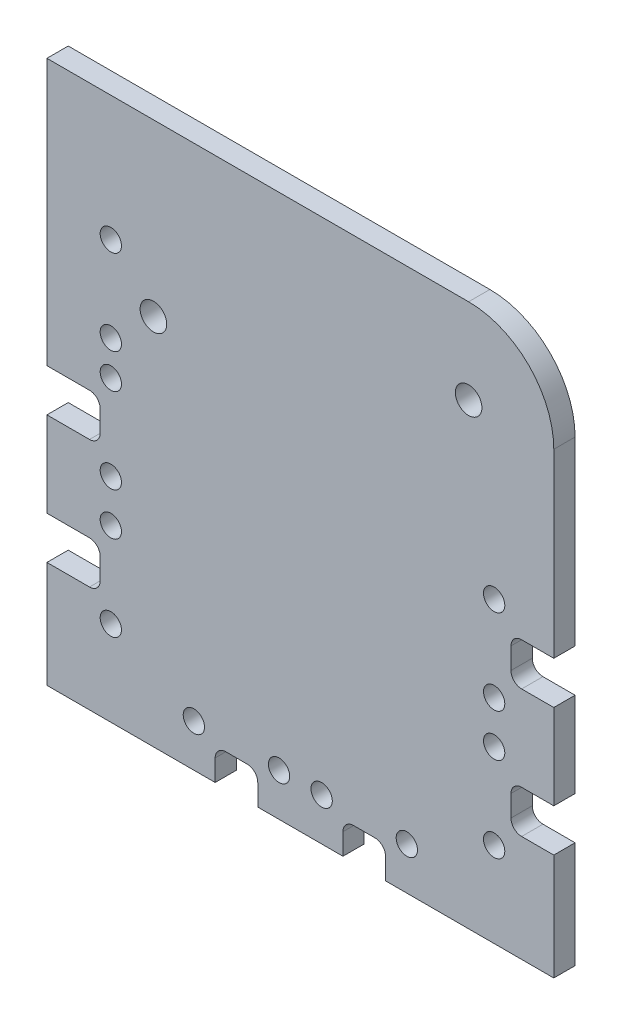
SolidWorks part; units mm, degrees
material "自訂玻璃纖維"
ref_plane "前基準面" through (0, 0, 0) normal (0, 0, 1) x (1, 0, 0)
ref_plane "上基準面" through (0, 0, 0) normal (0, 1, 0) x (1, 0, 0)
ref_plane "右基準面" through (0, 0, 0) normal (1, 0, 0) x (0, 0, -1)
sketch "草圖1" plane through (0, 0, 0) normal (0, 0, 1) x (1, 0, 0)
  line L0 (19.0581, -28.118) -> (19.0581, -12.618)
  line L1 (-28.5419, -12.618) -> (-28.5419, -28.118)
  line L2 (-28.5419, -28.118) -> (-28.5419, -29.618)
  line L3 (-28.5419, -5.618) -> (-28.5419, -12.618)
  line L4 (19.0581, -28.118) -> (19.0581, -29.618)
  line L5 (-12.7419, -55.618) -> (-12.7419, -53.618)
  line L6 (-7.5419, -4.618) -> (11.0581, -4.618)
  line L7 (-7.5419, -4.618) -> (-27.5419, -4.618)
  line L8 (-27.5419, -4.618) -> (-28.5419, -4.618)
  line L9 (-28.5419, -4.618) -> (-28.5419, -5.618)
  line L10 (19.0581, -52.618) -> (19.0581, -53.618)
  line L11 (-8.7419, -55.618) -> (-0.7419, -55.618)
  line L12 (-28.5419, -52.618) -> (-28.5419, -53.618)
  line L13 (-8.7419, -53.618) -> (-8.7419, -55.618)
  line L14 (-23.5419, -30.618) -> (-23.5419, -32.618)
  line L15 (-24.5419, -29.618) -> (-26.5419, -29.618)
  line L16 (-26.5419, -29.618) -> (-28.5419, -29.618)
  line L17 (-24.5419, -33.618) -> (-26.5419, -33.618)
  line L18 (-26.5419, -45.618) -> (-28.5419, -45.618)
  line L19 (-26.5419, -33.618) -> (-28.5419, -33.618)
  line L20 (-28.5419, -33.618) -> (-28.5419, -41.618)
  line L21 (-23.5419, -42.618) -> (-23.5419, -44.618)
  line L22 (-24.5419, -41.618) -> (-26.5419, -41.618)
  line L23 (-26.5419, -41.618) -> (-28.5419, -41.618)
  line L24 (-24.5419, -45.618) -> (-26.5419, -45.618)
  line L25 (-28.5419, -45.618) -> (-28.5419, -52.618)
  line L26 (15.0392, -30.618) -> (15.0392, -32.618)
  line L27 (16.0392, -29.618) -> (18.0392, -29.618)
  line L28 (18.0392, -29.618) -> (19.0581, -29.618)
  line L29 (16.0392, -33.618) -> (18.0392, -33.618)
  line L30 (16.0392, -41.618) -> (18.0392, -41.618)
  line L31 (16.0392, -45.618) -> (18.0392, -45.618)
  line L32 (19.0581, -33.618) -> (18.0392, -33.618)
  line L33 (19.0581, -33.618) -> (19.0581, -41.618)
  line L34 (19.0581, -45.618) -> (18.0392, -45.618)
  line L35 (18.0392, -41.618) -> (19.0581, -41.618)
  line L36 (15.0392, -42.618) -> (15.0392, -44.618)
  line L37 (19.0581, -45.618) -> (19.0581, -52.618)
  line L38 (-11.7419, -52.618) -> (-9.7419, -52.618)
  line L39 (3.2581, -53.618) -> (3.2581, -55.618)
  line L40 (-28.5419, -53.618) -> (-28.5419, -55.618)
  line L41 (-28.5419, -55.618) -> (-12.7419, -55.618)
  line L42 (19.0581, -53.618) -> (19.0581, -55.618)
  line L43 (-0.7419, -55.618) -> (-0.7419, -53.618)
  line L44 (0.2581, -52.618) -> (2.2581, -52.618)
  line L45 (3.2581, -55.618) -> (19.0581, -55.618)
  circle A0 centre (-18.5419, -20.618) radius 1.25
  circle A1 centre (-6.7419, -51.618) radius 1
  circle A2 centre (-14.7419, -51.618) radius 1
  circle A3 centre (5.2581, -51.618) radius 1
  circle A4 centre (-22.5419, -16.368) radius 1
  circle A5 centre (-22.5419, -24.368) radius 1
  arc A6 (19.0581, -12.618) -> (11.0581, -4.618) centre (11.0581, -12.618) ccw
  circle A7 centre (13.4581, -39.618) radius 1
  circle A8 centre (13.4581, -47.618) radius 1
  circle A9 centre (11.0581, -12.618) radius 1.25
  arc A10 (-24.5419, -29.618) -> (-23.5419, -30.618) centre (-24.5419, -30.618) cw
  arc A13 (-23.5419, -32.618) -> (-24.5419, -33.618) centre (-24.5419, -32.618) cw
  circle A14 centre (-22.5419, -27.618) radius 1
  circle A15 centre (-22.5419, -35.618) radius 1
  circle A18 centre (-2.7419, -51.618) radius 1
  circle A19 centre (-22.5419, -39.618) radius 1
  circle A20 centre (-22.5419, -47.618) radius 1
  circle A21 centre (13.4581, -27.618) radius 1
  circle A22 centre (13.4581, -35.618) radius 1
  arc A23 (-24.5419, -41.618) -> (-23.5419, -42.618) centre (-24.5419, -42.618) cw
  arc A24 (-23.5419, -44.618) -> (-24.5419, -45.618) centre (-24.5419, -44.618) cw
  arc A25 (16.0392, -29.618) -> (15.0392, -30.618) centre (16.0392, -30.618) ccw
  arc A26 (15.0392, -32.618) -> (16.0392, -33.618) centre (16.0392, -32.618) ccw
  arc A27 (15.0392, -44.618) -> (16.0392, -45.618) centre (16.0392, -44.618) ccw
  arc A28 (16.0392, -41.618) -> (15.0392, -42.618) centre (16.0392, -42.618) ccw
  arc A29 (-12.7419, -53.618) -> (-11.7419, -52.618) centre (-11.7419, -53.618) cw
  arc A30 (-9.7419, -52.618) -> (-8.7419, -53.618) centre (-9.7419, -53.618) cw
  arc A31 (2.2581, -52.618) -> (3.2581, -53.618) centre (2.2581, -53.618) cw
  arc A32 (-0.7419, -53.618) -> (0.2581, -52.618) centre (0.2581, -53.618) cw
  point P3 (11.0581, -12.618)
  point P9 (11.0581, -12.618)
  point P24 (-18.5419, -20.618)
  point P27 (-28.5419, -53.618)
  point P47 (-28.5419, -28.118)
  point P52 (11.0581, -12.618)
  point P70 (11.0581, -5.118)
  point P103 (17.0392, -41.618)
  dimension "D3" = 2.5
  dimension "D4" = 8
  dimension "D5" = 8
  dimension "D6" = 2
  dimension "D7" = 2.5
  dimension "D10" = 6
  dimension "D11" = 6
  dimension "D12" = 8
  dimension "D13" = 2
  dimension "D14" = 39
  dimension "D15" = 2
  dimension "D16" = 10
  dimension "D17" = 4
  dimension "D18" = 4
  dimension "D20" = 2
  dimension "D21" = 4
  dimension "D22" = 8
  dimension "D9" = 2
  dimension "D23" = 4
  dimension "D24" = 2
  dimension "D25" = 8
  dimension "D28" = 2
  dimension "D29" = 2
  dimension "D27" = 12
  dimension "D26" = 2
  dimension "D30" = 2
  dimension "D31" = 2
  dimension "D32" = 14
extrude "填料-伸長2" add sketch "草圖1" along normal blind 2
